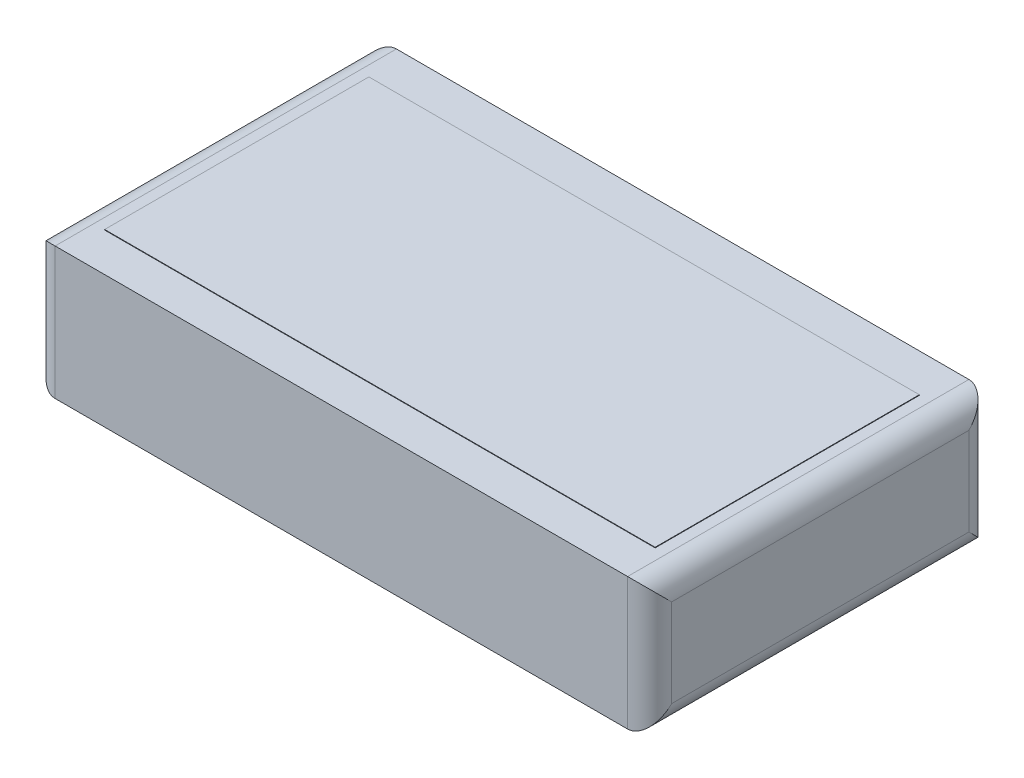
SolidWorks part; units mm, degrees
ref_plane "Plano frontal" through (0, 0, 0) normal (0, 0, 1) x (1, 0, 0)
ref_plane "Plano superior" through (0, 0, 0) normal (0, 1, 0) x (1, 0, 0)
ref_plane "Plano direito" through (0, 0, 0) normal (1, 0, 0) x (0, 0, -1)
sketch "Esboço1" plane through (0, 0, 0) normal (0, 0, 1) x (1, 0, 0)
  line L0 (-995.751, 0) -> (48791.8011, 0) construction
  line L1 (0, -995.751) -> (0, 48791.8011) construction
  line L2 (-28, 6) -> (28, 6)
  line L3 (28, 6) -> (28, -6)
  line L4 (28, -6) -> (-28, -6)
  line L5 (-28, 6) -> (-28, -6)
  line L6 (995.751, 0) -> (-48791.8011, 0) construction
  point P4 (0, -6)
  point P13 (0, 6)
  dimension "D1" = 28
  dimension "D2" = 12
extrude "Ressalto-extrusão3" add sketch "Esboço1" along normal blind 31
sketch "Esboço5" plane through (0, 6, 0) normal (0, 1, 0) x (1, 0, 0)
  line L0 (28, -31) -> (28, 0) construction
  line L1 (-24.545, -3.5) -> (25.455, -3.5)
  line L2 (-24.545, -3.5) -> (-24.545, -27.5)
  line L3 (-24.545, -27.5) -> (25.455, -27.5)
  line L4 (25.455, -3.5) -> (25.455, -27.5)
  line L5 (28, -31) -> (-28, -31) construction
  dimension "D1" = 24
  dimension "D2" = 50
  dimension "D3" = 2.545
  dimension "D4" = 3.5
sketch "Esboço7" plane through (0, 6, 0) normal (0, 1, 0) x (1, 0, 0)
  line L0 (28, -31) -> (-28, -31) construction
  line L1 (-25, -3.5) -> (25, -3.5)
  line L2 (-25, -3.5) -> (-25, -27.5)
  line L3 (-25, -27.5) -> (25, -27.5)
  line L4 (25, -3.5) -> (25, -27.5)
  line L5 (28, -31) -> (28, 0) construction
  dimension "D1" = 50
  dimension "D2" = 24
  dimension "D3" = 3.5
  dimension "D4" = 3
extrude "Ressalto-extrusão4" add sketch "Esboço7" along normal blind 0.05
fillet "Filete2" radius 2 4 edges at (28, -6, 15.5) (28, 0, 31) (28, 6, 15.5) (28, 0, 0)
fillet "Filete3" radius 2 4 edges at (-28, 6, 15.5) (-28, 0, 31) (-28, -6, 15.5) (-28, 0, 0)
